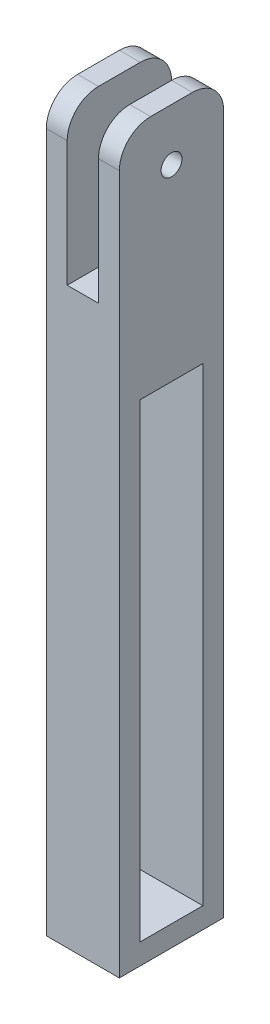
SolidWorks part; units mm, degrees
ref_plane "Front Plane" through (0, 0, 0) normal (0, 0, 1) x (1, 0, 0)
ref_plane "Top Plane" through (0, 0, 0) normal (0, 1, 0) x (1, 0, 0)
ref_plane "Right Plane" through (0, 0, 0) normal (1, 0, 0) x (0, 0, -1)
sketch "Sketch1" plane through (0, 0, 0) normal (0, 1, 0) x (1, 0, 0)
  line L1 (0, 0) -> (35, 0)
  line L2 (0, 0) -> (0, 50)
  line L3 (0, 50) -> (35, 50)
  line L4 (35, 0) -> (35, 50)
  dimension "D1" = 35
  dimension "D2" = 50
extrude "Boss-Extrude1" add sketch "Sketch1" along normal blind 350
sketch "Sketch2" plane through (35, 0, 0) normal (1, 0, 0) x (0, 0, -1)
  line L0 (0, 350) -> (0, 0) construction
  line L1 (15, 350) -> (0, 350)
  line L2 (0, 350) -> (0, 335)
  line L3 (35, 350) -> (50, 350)
  line L4 (0, 0) -> (50, 0)
  line L5 (50, 0) -> (50, 350)
  line L6 (50, 350) -> (0, 350)
  line L7 (0, 350) -> (0, 0)
  line L10 (35, 350) -> (15, 350)
  line L12 (50, 350) -> (50, 335)
  arc A0 (50, 335) -> (35, 350) centre (35, 335) ccw
  arc A1 (15, 350) -> (0, 335) centre (15, 335) ccw
  line M10 (50, 0) -> (50, 350)
  line M11 (50, 350) -> (0, 350)
  line M12 (0, 350) -> (0, 0)
  dimension "D2" = 15
  dimension "D4" = 20
  dimension "D3" = 50
  dimension "D5" = 15
  dimension "D6" = 15
  dimension "D1" = 0
extrude "Cut-Extrude1" cut sketch "Sketch2" against normal blind 350 contours A1 M11 M12 | A0 M10 M11
sketch "Sketch3" plane through (35, 0, 0) normal (1, 0, 0) x (0, 0, -1)
  line L0 (0, 0) -> (50, 0) construction
  line L1 (10, 235) -> (40, 235)
  line L2 (10, 235) -> (10, 10)
  line L3 (10, 10) -> (40, 10)
  line L4 (40, 235) -> (40, 10)
  line L5 (10, 235) -> (40, 10) construction
  line L6 (10, 10) -> (40, 235) construction
  line L7 (15, 350) -> (35, 350) construction
  point P0 (25, 122.5)
  point P9 (25, 350)
  dimension "D1" = 10
  dimension "D2" = 225
  dimension "D3" = 30
extrude "Cut-Extrude2" cut sketch "Sketch3" against normal blind 350
sketch "Sketch4" plane through (0, 0, 0) normal (0, 0, 1) x (1, 0, 0)
  line L0 (0, 350) -> (35, 350) construction
  line L1 (10, 350) -> (25, 350)
  line L2 (10, 350) -> (10, 275)
  line L3 (10, 275) -> (25, 275)
  line L4 (25, 275) -> (25, 350)
  line L5 (0, 335) -> (0, 0) construction
  dimension "D1" = 75
  dimension "D2" = 15
  dimension "D3" = 10
extrude "Cut-Extrude3" cut sketch "Sketch4" against normal blind 350
sketch "Sketch5" plane through (0, 0, 0) normal (-1, 0, 0) x (0, 0, 1)
  line L0 (-40, 235) -> (-10, 235) construction
  circle A0 centre (-25, 325) radius 5
  point P4 (-25, 235)
  point P5 (-25, 321.6283)
  point P6 (-25, 317.1061)
  dimension "D1" = 10
  dimension "D2" = 10
extrude "Cut-Extrude4" cut sketch "Sketch5" against normal through all
